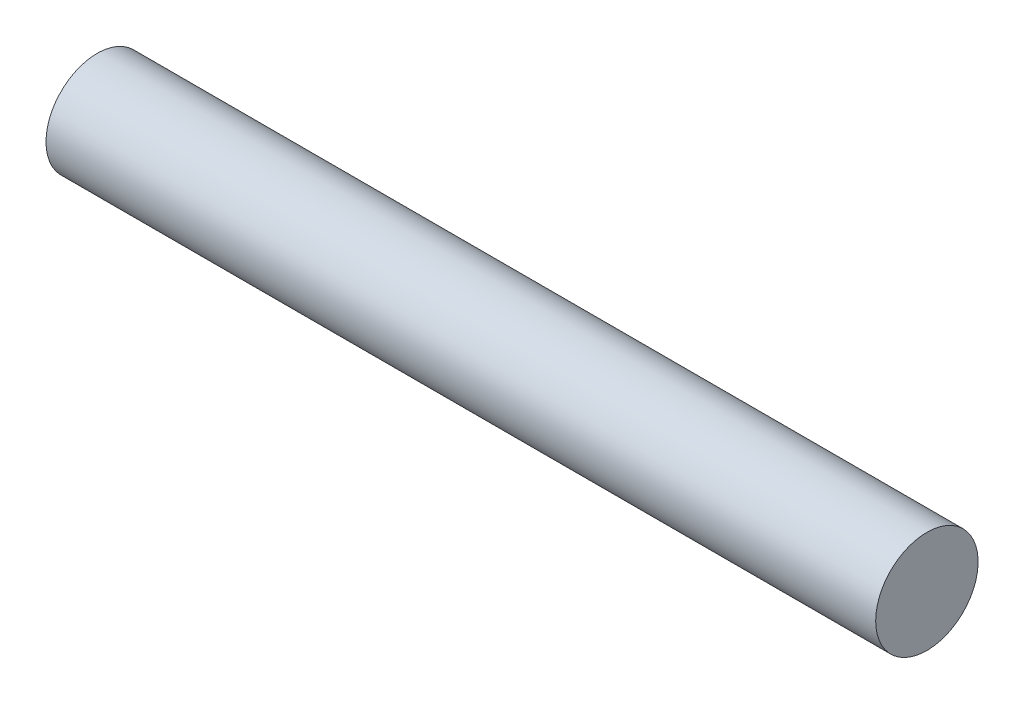
SolidWorks part; units mm, degrees
material "1060 Alloy"
ref_plane "Front Plane" through (0, 0, 0) normal (0, 0, 1) x (1, 0, 0)
ref_plane "Top Plane" through (0, 0, 0) normal (0, 1, 0) x (1, 0, 0)
ref_plane "Right Plane" through (0, 0, 0) normal (1, 0, 0) x (0, 0, -1)
sketch "Sketch1" plane through (0, 0, 0) normal (0, 0, 1) x (1, 0, 0)
  line L1 (-81, 5) -> (81, 5)
  line L2 (-81, 5) -> (-81, -5)
  line L3 (-81, -5) -> (81, -5)
  line L4 (81, 5) -> (81, -5)
  point P7 (29.1109, -168.275)
  point P9 (0, 0)
  dimension "D1" = 5
  dimension "D2" = 5
  dimension "D3" = 81
  dimension "D4" = 81
revolve "Revolve1" add sketch "Sketch1" angle 360 about L3
